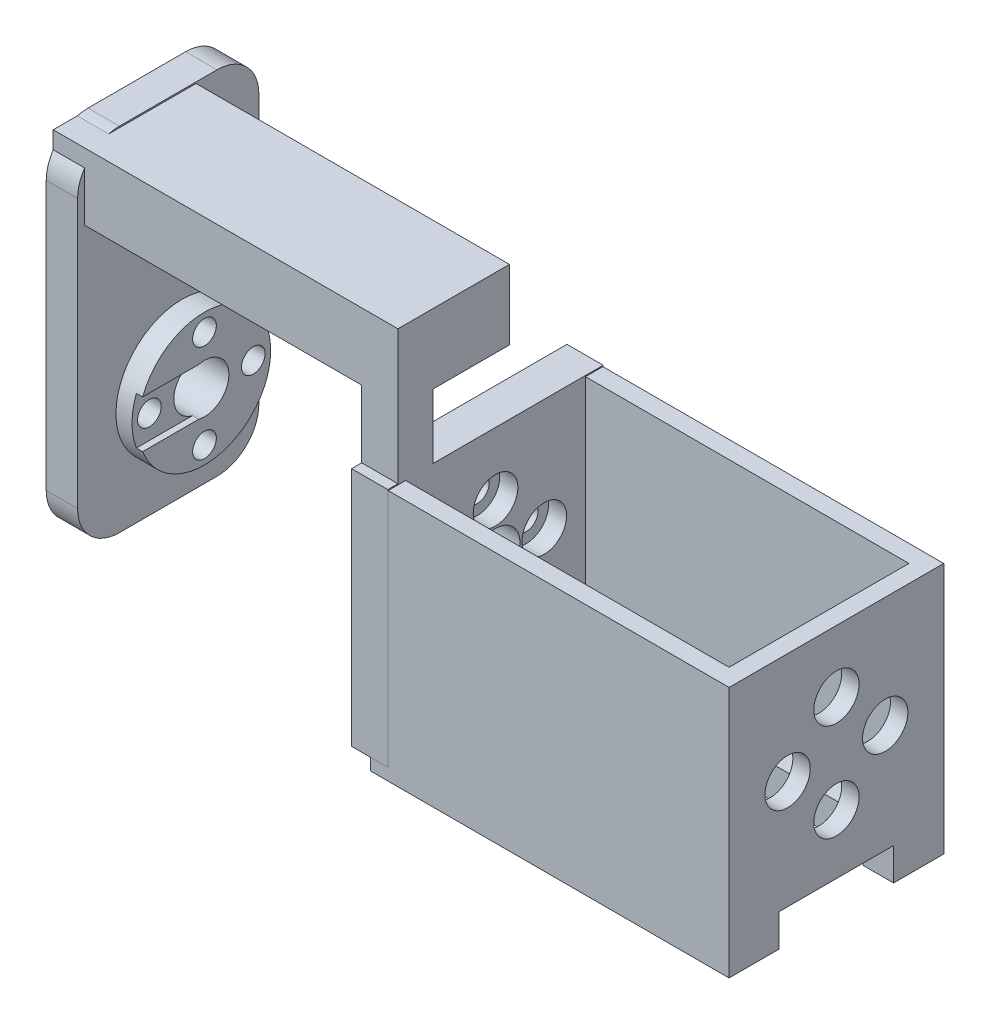
SolidWorks part; units mm, degrees
ref_plane "Front Plane" through (0, 0, 0) normal (0, 0, 1) x (1, 0, 0)
ref_plane "Top Plane" through (0, 0, 0) normal (0, 1, 0) x (1, 0, 0)
ref_plane "Right Plane" through (0, 0, 0) normal (1, 0, 0) x (0, 0, -1)
ref_plane "PX_m15_900" through (-15.9, 0, 0) normal (1, 0, 0) x (0, 0, -1)
sketch "S_prism1" plane through (-15.9, 0, 0) normal (1, 0, 0) x (0, 0, -1)
  line L0 (15.45, -18.45) -> (15.45, 16.05)
  line L1 (15.45, 16.05) -> (-15.45, 16.05)
  line L2 (-15.45, 16.05) -> (-15.45, -18.45)
  line L3 (-15.45, -18.45) -> (15.45, -18.45)
extrude "Boss_1" add sketch "S_prism1" along normal blind 5.2
ref_plane "PX_m55_650" through (-55.65, 0, 0) normal (1, 0, 0) x (0, 0, -1)
sketch "S_cyl2" plane through (-55.65, 0, 0) normal (1, 0, 0) x (0, 0, -1)
  circle A0 centre (0, 0) radius 9.5
  dimension "D1_S_cyl2" = 19
extrude "Boss_2" add sketch "S_cyl2" along normal blind 3.2
ref_plane "PX_m60_150" through (-60.15, 0, 0) normal (1, 0, 0) x (0, 0, -1)
sketch "S_prism3" plane through (-60.15, 0, 0) normal (1, 0, 0) x (0, 0, -1)
  line L0 (11, -9) -> (11, 29.5)
  line L1 (5, 35.5) -> (-9, 35.5)
  line L2 (-15, 29.5) -> (-15, -9)
  line L3 (-9, -15) -> (5, -15)
  arc A0 (5, -15) -> (11, -9) centre (4.9999, -8.9999) ccw
  arc A1 (11, 29.5) -> (5, 35.5) centre (4.9999, 29.4999) ccw
  arc A2 (-9, 35.5) -> (-15, 29.5) centre (-8.9999, 29.4999) ccw
  arc A3 (-15, -9) -> (-9, -15) centre (-8.9999, -8.9999) ccw
extrude "Boss_3" add sketch "S_prism3" along normal blind 4.5
ref_plane "PZ_m15_400" through (0, 0, -15.4) normal (0, 0, 1) x (1, 0, 0)
sketch "S_box4" plane through (0, 0, -15.4) normal (0, 0, 1) x (1, 0, 0)
  line L0 (-13.2, -20.2) -> (-10.7, -20.2)
  line L1 (-10.7, -20.2) -> (-10.7, 15.9)
  line L2 (-10.7, 15.9) -> (-13.2, 15.9)
  line L3 (-13.2, 15.9) -> (-13.2, -20.2)
  dimension "P1" = 13.2
  dimension "P2" = 20.2
  dimension "P3" = 10.7
  dimension "P4" = 20.2
  dimension "P5" = 10.7
  dimension "P6" = 15.9
  dimension "P7" = 13.2
  dimension "P8" = 15.9
extrude "Boss_4" add sketch "S_box4" along normal blind 30.8
sketch "S_box5" plane through (0, 0, -15.4) normal (0, 0, 1) x (1, 0, 0)
  line L0 (35.7, -20.2) -> (38.2, -20.2)
  line L1 (38.2, -20.2) -> (38.2, 15.9)
  line L2 (38.2, 15.9) -> (35.7, 15.9)
  line L3 (35.7, 15.9) -> (35.7, -20.2)
  dimension "P1" = 35.7
  dimension "P2" = 20.2
  dimension "P3" = 38.2
  dimension "P4" = 20.2
  dimension "P5" = 38.2
  dimension "P6" = 15.9
  dimension "P7" = 35.7
  dimension "P8" = 15.9
extrude "Boss_5" add sketch "S_box5" along normal blind 30.8
sketch "S_box6" plane through (0, 0, -15.4) normal (0, 0, 1) x (1, 0, 0)
  line L0 (-13.2, -20.2) -> (38.2, -20.2)
  line L1 (38.2, -20.2) -> (38.2, 15.9)
  line L2 (38.2, 15.9) -> (-13.2, 15.9)
  line L3 (-13.2, 15.9) -> (-13.2, -20.2)
  dimension "P1" = 13.2
  dimension "P2" = 20.2
  dimension "P3" = 38.2
  dimension "P4" = 20.2
  dimension "P5" = 38.2
  dimension "P6" = 15.9
  dimension "P7" = 13.2
  dimension "P8" = 15.9
extrude "Boss_6" add sketch "S_box6" along normal blind 2.5
ref_plane "PZ_p12_900" through (0, 0, 12.9) normal (0, 0, 1) x (1, 0, 0)
sketch "S_box7" plane through (0, 0, 12.9) normal (0, 0, 1) x (1, 0, 0)
  line L0 (-13.2, -20.2) -> (38.2, -20.2)
  line L1 (38.2, -20.2) -> (38.2, 15.9)
  line L2 (38.2, 15.9) -> (-13.2, 15.9)
  line L3 (-13.2, 15.9) -> (-13.2, -20.2)
  dimension "P1" = 13.2
  dimension "P2" = 20.2
  dimension "P3" = 38.2
  dimension "P4" = 20.2
  dimension "P5" = 38.2
  dimension "P6" = 15.9
  dimension "P7" = 13.2
  dimension "P8" = 15.9
extrude "Boss_7" add sketch "S_box7" along normal blind 2.5
sketch "S_box8" plane through (0, 0, -15.4) normal (0, 0, 1) x (1, 0, 0)
  line L0 (-13.2, -20.2) -> (38.2, -20.2)
  line L1 (38.2, -20.2) -> (38.2, -15.6)
  line L2 (38.2, -15.6) -> (-13.2, -15.6)
  line L3 (-13.2, -15.6) -> (-13.2, -20.2)
  dimension "P1" = 13.2
  dimension "P2" = 20.2
  dimension "P3" = 38.2
  dimension "P4" = 20.2
  dimension "P5" = 38.2
  dimension "P6" = 15.6
  dimension "P7" = 13.2
  dimension "P8" = 15.6
extrude "Boss_8" add sketch "S_box8" along normal blind 30.8
ref_plane "PZ_p9_000" through (0, 0, 9) normal (0, 0, 1) x (1, 0, 0)
sketch "S_box9" plane through (0, 0, 9) normal (0, 0, 1) x (1, 0, 0)
  line L0 (-15.9, 16) -> (-10.7, 16)
  line L1 (-10.7, 16) -> (-10.7, 25.8)
  line L2 (-10.7, 25.8) -> (-15.9, 25.8)
  line L3 (-15.9, 25.8) -> (-15.9, 16)
  dimension "P1" = 15.9
  dimension "P2" = 16
  dimension "P3" = 10.7
  dimension "P4" = 16
  dimension "P5" = 10.7
  dimension "P6" = 25.8
  dimension "P7" = 15.9
  dimension "P8" = 25.8
extrude "Boss_9" add sketch "S_box9" along normal blind 5
ref_plane "PZ_m2_000" through (0, 0, -2) normal (0, 0, 1) x (1, 0, 0)
sketch "S_box10" plane through (0, 0, -2) normal (0, 0, 1) x (1, 0, 0)
  line L0 (-15.9, 25.3) -> (-10.7, 25.3)
  line L1 (-10.7, 25.3) -> (-10.7, 35.3)
  line L2 (-10.7, 35.3) -> (-15.9, 35.3)
  line L3 (-15.9, 35.3) -> (-15.9, 25.3)
  dimension "P1" = 15.9
  dimension "P2" = 25.3
  dimension "P3" = 10.7
  dimension "P4" = 25.3
  dimension "P5" = 10.7
  dimension "P6" = 35.3
  dimension "P7" = 15.9
  dimension "P8" = 35.3
extrude "Boss_10" add sketch "S_box10" along normal blind 16
sketch "S_box11" plane through (0, 0, -2) normal (0, 0, 1) x (1, 0, 0)
  line L0 (-60.15, 25.7) -> (-10.7, 25.7)
  line L1 (-10.7, 25.7) -> (-10.7, 35.3)
  line L2 (-10.7, 35.3) -> (-60.15, 35.3)
  line L3 (-60.15, 35.3) -> (-60.15, 25.7)
  dimension "P1" = 60.15
  dimension "P2" = 25.7
  dimension "P3" = 10.7
  dimension "P4" = 25.7
  dimension "P5" = 10.7
  dimension "P6" = 35.3
  dimension "P7" = 60.15
  dimension "P8" = 35.3
extrude "Boss_11" add sketch "S_box11" along normal blind 16
ref_plane "PX_m16_000" through (-16, 0, 0) normal (1, 0, 0) x (0, 0, -1)
sketch "S_hole12" plane through (-16, 0, 0) normal (1, 0, 0) x (0, 0, -1)
  circle A0 centre (0, 0) radius 3.5
  dimension "D1_S_hole12" = 7
extrude "Hole_12" cut sketch "S_hole12" along normal blind 5.4
sketch "S_hole13" plane through (-16, 0, 0) normal (1, 0, 0) x (0, 0, -1)
  circle A0 centre (0, 7) radius 1.7
  dimension "D1_S_hole13" = 3.4
  dimension "P2" = 7
extrude "Hole_13" cut sketch "S_hole13" along normal blind 5.4
sketch "S_hole14" plane through (-16, 0, 0) normal (1, 0, 0) x (0, 0, -1)
  circle A0 centre (-7, 0) radius 1.7
  dimension "D1_S_hole14" = 3.4
  dimension "P2" = 7
extrude "Hole_14" cut sketch "S_hole14" along normal blind 5.4
sketch "S_hole15" plane through (-16, 0, 0) normal (1, 0, 0) x (0, 0, -1)
  circle A0 centre (0, -7) radius 1.7
  dimension "D1_S_hole15" = 3.4
  dimension "P2" = 7
extrude "Hole_15" cut sketch "S_hole15" along normal blind 5.4
sketch "S_hole16" plane through (-16, 0, 0) normal (1, 0, 0) x (0, 0, -1)
  circle A0 centre (7, 0) radius 1.7
  dimension "D1_S_hole16" = 3.4
  dimension "P2" = 7
extrude "Hole_16" cut sketch "S_hole16" along normal blind 5.4
ref_plane "PX_m13_300" through (-13.3, 0, 0) normal (1, 0, 0) x (0, 0, -1)
sketch "S_hole17" plane through (-13.3, 0, 0) normal (1, 0, 0) x (0, 0, -1)
  circle A0 centre (0, 7) radius 3.2
  dimension "D1_S_hole17" = 6.4
  dimension "P2" = 7
extrude "Hole_17" cut sketch "S_hole17" along normal blind 2.7
sketch "S_hole18" plane through (-13.3, 0, 0) normal (1, 0, 0) x (0, 0, -1)
  circle A0 centre (-7, 0) radius 3.2
  dimension "D1_S_hole18" = 6.4
  dimension "P2" = 7
extrude "Hole_18" cut sketch "S_hole18" along normal blind 2.7
sketch "S_hole19" plane through (-13.3, 0, 0) normal (1, 0, 0) x (0, 0, -1)
  circle A0 centre (0, -7) radius 3.2
  dimension "D1_S_hole19" = 6.4
  dimension "P2" = 7
extrude "Hole_19" cut sketch "S_hole19" along normal blind 2.7
sketch "S_hole20" plane through (-13.3, 0, 0) normal (1, 0, 0) x (0, 0, -1)
  circle A0 centre (7, 0) radius 3.2
  dimension "D1_S_hole20" = 6.4
  dimension "P2" = 7
extrude "Hole_20" cut sketch "S_hole20" along normal blind 2.7
ref_plane "PX_m60_250" through (-60.25, 0, 0) normal (1, 0, 0) x (0, 0, -1)
sketch "S_hole21" plane through (-60.25, 0, 0) normal (1, 0, 0) x (0, 0, -1)
  circle A0 centre (0, 0) radius 3.5
  dimension "D1_S_hole21" = 7
extrude "Hole_21" cut sketch "S_hole21" along normal blind 7.9
sketch "S_hole22" plane through (-60.25, 0, 0) normal (1, 0, 0) x (0, 0, -1)
  circle A0 centre (0, 7) radius 1.7
  dimension "D1_S_hole22" = 3.4
  dimension "P2" = 7
extrude "Hole_22" cut sketch "S_hole22" along normal blind 7.9
sketch "S_hole23" plane through (-60.25, 0, 0) normal (1, 0, 0) x (0, 0, -1)
  circle A0 centre (-7, 0) radius 1.7
  dimension "D1_S_hole23" = 3.4
  dimension "P2" = 7
extrude "Hole_23" cut sketch "S_hole23" along normal blind 7.9
sketch "S_hole24" plane through (-60.25, 0, 0) normal (1, 0, 0) x (0, 0, -1)
  circle A0 centre (0, -7) radius 1.7
  dimension "D1_S_hole24" = 3.4
  dimension "P2" = 7
extrude "Hole_24" cut sketch "S_hole24" along normal blind 7.9
sketch "S_hole25" plane through (-60.25, 0, 0) normal (1, 0, 0) x (0, 0, -1)
  circle A0 centre (7, 0) radius 1.7
  dimension "D1_S_hole25" = 3.4
  dimension "P2" = 7
extrude "Hole_25" cut sketch "S_hole25" along normal blind 7.9
sketch "S_hole26" plane through (-60.25, 0, 0) normal (1, 0, 0) x (0, 0, -1)
  circle A0 centre (0, 7) radius 3.2
  dimension "D1_S_hole26" = 6.4
  dimension "P2" = 7
extrude "Hole_26" cut sketch "S_hole26" along normal blind 2.1
sketch "S_hole27" plane through (-60.25, 0, 0) normal (1, 0, 0) x (0, 0, -1)
  circle A0 centre (-7, 0) radius 3.2
  dimension "D1_S_hole27" = 6.4
  dimension "P2" = 7
extrude "Hole_27" cut sketch "S_hole27" along normal blind 2.1
sketch "S_hole28" plane through (-60.25, 0, 0) normal (1, 0, 0) x (0, 0, -1)
  circle A0 centre (0, -7) radius 3.2
  dimension "D1_S_hole28" = 6.4
  dimension "P2" = 7
extrude "Hole_28" cut sketch "S_hole28" along normal blind 2.1
sketch "S_hole29" plane through (-60.25, 0, 0) normal (1, 0, 0) x (0, 0, -1)
  circle A0 centre (7, 0) radius 3.2
  dimension "D1_S_hole29" = 6.4
  dimension "P2" = 7
extrude "Hole_29" cut sketch "S_hole29" along normal blind 2.1
sketch "S_cut30" plane through (0, 0, 0) normal (0, 0, 1) x (1, 0, 0)
  line L0 (-53.35, -3.4) -> (-52.35, -3.4)
  line L1 (-52.35, -3.4) -> (-52.35, 3.4)
  line L2 (-52.35, 3.4) -> (-53.35, 3.4)
  line L3 (-53.35, 3.4) -> (-53.35, -3.4)
  dimension "P1" = 53.35
  dimension "P2" = 3.4
  dimension "P3" = 52.35
  dimension "P4" = 3.4
  dimension "P5" = 52.35
  dimension "P6" = 3.4
  dimension "P7" = 53.35
  dimension "P8" = 3.4
extrude "Pocket_30" cut sketch "S_cut30" along normal blind 10
ref_plane "PY_m20_300" through (0, -20.3, 0) normal (0, 1, 0) x (1, 0, 0)
sketch "S_hole31" plane through (0, -20.3, 0) normal (0, 1, 0) x (1, 0, 0)
  circle A0 centre (0, 0) radius 10.5
  dimension "D1_S_hole31" = 21
extrude "Hole_31" cut sketch "S_hole31" along normal blind 4.8
ref_plane "PZ_m9_700" through (0, 0, -9.7) normal (0, 0, 1) x (1, 0, 0)
sketch "S_cut32" plane through (0, 0, -9.7) normal (0, 0, 1) x (1, 0, 0)
  line L0 (10.9, -20.3) -> (30.4, -20.3)
  line L1 (30.4, -20.3) -> (30.4, -15.55)
  line L2 (30.4, -15.55) -> (10.9, -15.55)
  line L3 (10.9, -15.55) -> (10.9, -20.3)
  dimension "P1" = 10.9
  dimension "P2" = 20.3
  dimension "P3" = 30.4
  dimension "P4" = 20.3
  dimension "P5" = 30.4
  dimension "P6" = 15.55
  dimension "P7" = 10.9
  dimension "P8" = 15.55
extrude "Pocket_32" cut sketch "S_cut32" along normal blind 19.4
ref_plane "PZ_m8_200" through (0, 0, -8.2) normal (0, 0, 1) x (1, 0, 0)
sketch "S_cut33" plane through (0, 0, -8.2) normal (0, 0, 1) x (1, 0, 0)
  line L0 (30.4, -20.3) -> (38.7, -20.3)
  line L1 (38.7, -20.3) -> (38.7, -15.55)
  line L2 (38.7, -15.55) -> (30.4, -15.55)
  line L3 (30.4, -15.55) -> (30.4, -20.3)
  dimension "P1" = 30.4
  dimension "P2" = 20.3
  dimension "P3" = 38.7
  dimension "P4" = 20.3
  dimension "P5" = 38.7
  dimension "P6" = 15.55
  dimension "P7" = 30.4
  dimension "P8" = 15.55
extrude "Pocket_33" cut sketch "S_cut33" along normal blind 16.4
ref_plane "PZ_m3_500" through (0, 0, -3.5) normal (0, 0, 1) x (1, 0, 0)
sketch "S_cut34" plane through (0, 0, -3.5) normal (0, 0, 1) x (1, 0, 0)
  line L0 (0, -20.3) -> (11, -20.3)
  line L1 (11, -20.3) -> (11, -15.55)
  line L2 (11, -15.55) -> (0, -15.55)
  line L3 (0, -15.55) -> (0, -20.3)
  dimension "P1" = 20.3
  dimension "P2" = 11
  dimension "P3" = 20.3
  dimension "P4" = 11
  dimension "P5" = 15.55
  dimension "P6" = 15.55
extrude "Pocket_34" cut sketch "S_cut34" along normal blind 7
ref_plane "PZ_m15_900" through (0, 0, -15.9) normal (0, 0, 1) x (1, 0, 0)
sketch "S_cut35" plane through (0, 0, -15.9) normal (0, 0, 1) x (1, 0, 0)
  line L0 (-10, -20.4) -> (10, -20.4)
  line L1 (10, -20.4) -> (10, -17.5)
  line L2 (10, -17.5) -> (-10, -17.5)
  line L3 (-10, -17.5) -> (-10, -20.4)
  dimension "P1" = 10
  dimension "P2" = 20.4
  dimension "P3" = 10
  dimension "P4" = 20.4
  dimension "P5" = 10
  dimension "P6" = 17.5
  dimension "P7" = 10
  dimension "P8" = 17.5
extrude "Pocket_35" cut sketch "S_cut35" along normal blind 15.9
sketch "S_hole36" plane through (0, -20.3, 0) normal (0, 1, 0) x (1, 0, 0)
  circle A0 centre (8.3, -10.25) radius 1.1
  dimension "D1_S_hole36" = 2.2
  dimension "P2" = 8.3
  dimension "P3" = 10.25
extrude "Hole_36" cut sketch "S_hole36" along normal blind 4.8
sketch "S_hole37" plane through (0, -20.3, 0) normal (0, 1, 0) x (1, 0, 0)
  circle A0 centre (8.3, -10.25) radius 2.3
  dimension "D1_S_hole37" = 4.6
  dimension "P2" = 8.3
  dimension "P3" = 10.25
extrude "Hole_37" cut sketch "S_hole37" along normal blind 1.7
sketch "S_hole38" plane through (0, -20.3, 0) normal (0, 1, 0) x (1, 0, 0)
  circle A0 centre (32.75, 10.25) radius 1.1
  dimension "D1_S_hole38" = 2.2
  dimension "P2" = 32.75
  dimension "P3" = 10.25
extrude "Hole_38" cut sketch "S_hole38" along normal blind 4.8
sketch "S_hole39" plane through (0, -20.3, 0) normal (0, 1, 0) x (1, 0, 0)
  circle A0 centre (32.75, 10.25) radius 2.3
  dimension "D1_S_hole39" = 4.6
  dimension "P2" = 32.75
  dimension "P3" = 10.25
extrude "Hole_39" cut sketch "S_hole39" along normal blind 1.7
sketch "S_hole40" plane through (0, -20.3, 0) normal (0, 1, 0) x (1, 0, 0)
  circle A0 centre (32.75, -10.25) radius 1.1
  dimension "D1_S_hole40" = 2.2
  dimension "P2" = 32.75
  dimension "P3" = 10.25
extrude "Hole_40" cut sketch "S_hole40" along normal blind 4.8
sketch "S_hole41" plane through (0, -20.3, 0) normal (0, 1, 0) x (1, 0, 0)
  circle A0 centre (32.75, -10.25) radius 2.3
  dimension "D1_S_hole41" = 4.6
  dimension "P2" = 32.75
  dimension "P3" = 10.25
extrude "Hole_41" cut sketch "S_hole41" along normal blind 1.7
ref_plane "PX_p35_600" through (35.6, 0, 0) normal (1, 0, 0) x (0, 0, -1)
sketch "S_hole42" plane through (35.6, 0, 0) normal (1, 0, 0) x (0, 0, -1)
  circle A0 centre (0, 7) radius 3.25
  dimension "D1_S_hole42" = 6.5
  dimension "P2" = 7
extrude "Hole_42" cut sketch "S_hole42" along normal blind 2.7
sketch "S_hole43" plane through (35.6, 0, 0) normal (1, 0, 0) x (0, 0, -1)
  circle A0 centre (-7, 0) radius 3.25
  dimension "D1_S_hole43" = 6.5
  dimension "P2" = 7
extrude "Hole_43" cut sketch "S_hole43" along normal blind 2.7
sketch "S_hole44" plane through (35.6, 0, 0) normal (1, 0, 0) x (0, 0, -1)
  circle A0 centre (0, -7) radius 3.25
  dimension "D1_S_hole44" = 6.5
  dimension "P2" = 7
extrude "Hole_44" cut sketch "S_hole44" along normal blind 2.7
sketch "S_hole45" plane through (35.6, 0, 0) normal (1, 0, 0) x (0, 0, -1)
  circle A0 centre (7, 0) radius 3.25
  dimension "D1_S_hole45" = 6.5
  dimension "P2" = 7
extrude "Hole_45" cut sketch "S_hole45" along normal blind 2.7
equation "\"plate_t\" = 3"
equation "\"clearance\" = 0.5"
